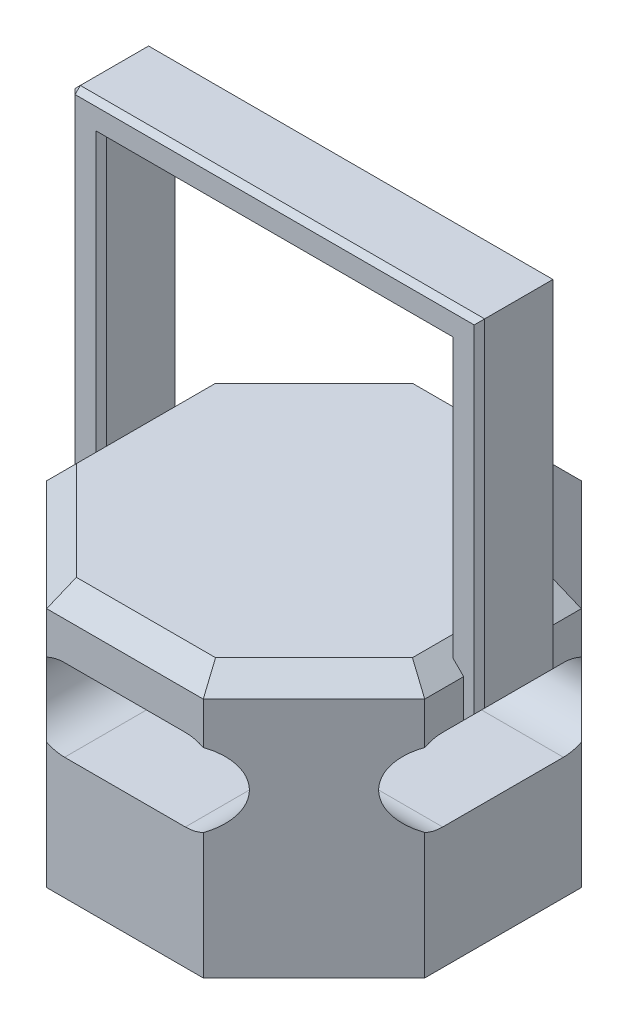
SolidWorks part; units mm, degrees
ref_plane "Front Plane" through (0, 0, 0) normal (0, 0, 1) x (1, 0, 0)
ref_plane "Top Plane" through (0, 0, 0) normal (0, 1, 0) x (1, 0, 0)
ref_plane "Right Plane" through (0, 0, 0) normal (1, 0, 0) x (0, 0, -1)
sketch "Sketch1" plane through (0, 0, 0) normal (0, 1, 0) x (1, 0, 0)
  line L1 (14.9117, 36) -> (-14.9117, 36)
  line L2 (-14.9117, 36) -> (-36, 14.9117)
  line L3 (-36, 14.9117) -> (-36, -14.9117)
  line L4 (-36, -14.9117) -> (-14.9117, -36)
  line L5 (-14.9117, -36) -> (14.9117, -36)
  line L6 (14.9117, -36) -> (36, -14.9117)
  line L7 (36, -14.9117) -> (36, 14.9117)
  line L8 (36, 14.9117) -> (14.9117, 36)
  circle A0 centre (0, 0) radius 36 construction
  dimension "D1" = 72
extrude "Boss-Extrude1" add sketch "Sketch1" along normal blind 50
sketch "Sketch18" plane through (0, 50, 0) normal (0, 1, 0) x (1, 0, 0)
  line L2 (-39, 7.5) -> (-39, -7.5)
  line L5 (-36, 14.9117) -> (-36, -14.9117) construction
  line L12 (-39, 7.5) -> (-33, 7.5)
  line L14 (-33, 7.5) -> (-33, -7.5)
  line L15 (-33, -7.5) -> (-39, -7.5)
  line L16 (0, -27.5) -> (0, 27.5) construction
  line L17 (33, 7.5) -> (33, -7.5)
  line L18 (39, 7.5) -> (33, 7.5)
  line L19 (39, 7.5) -> (39, -7.5)
  line L20 (33, -7.5) -> (39, -7.5)
  point P1 (-33, 0)
  dimension "D1" = 15
  dimension "D2" = 6
  dimension "D3" = 6
  dimension "D4" = 3
sketch "Sketch3" plane through (0, 0, 36) normal (0, 0, 1) x (1, 0, 0)
  line L0 (-11.5, 31) -> (11.5, 31) construction
  line L1 (-11.5, 38.8) -> (11.5, 38.8)
  line L2 (-11.5, 23.2) -> (11.5, 23.2)
  line L4 (-14.9117, 50) -> (14.9117, 50) construction
  arc A0 (-11.5, 38.8) -> (-11.5, 23.2) centre (-11.5, 31) ccw
  arc A1 (11.5, 23.2) -> (11.5, 38.8) centre (11.5, 31) ccw
  point P2 (0, 31)
  dimension "D1" = 7.8
  dimension "D2" = 23
  dimension "D3" = 19
extrude "Cut-Extrude1" cut sketch "Sketch3" against normal blind 72
sketch "Sketch4" plane through (-36, 0, 0) normal (-1, 0, 0) x (0, 0, 1)
  line L0 (-11.5, 31) -> (11.5, 31) construction
  line L1 (-11.5, 38.8) -> (11.5, 38.8)
  line L2 (-11.5, 23.2) -> (11.5, 23.2)
  line L4 (-14.9117, 50) -> (14.9117, 50) construction
  arc A0 (-11.5, 38.8) -> (-11.5, 23.2) centre (-11.5, 31) ccw
  arc A1 (11.5, 23.2) -> (11.5, 38.8) centre (11.5, 31) ccw
  point P2 (0, 31)
  dimension "D1" = 7.8
  dimension "D2" = 19
  dimension "D3" = 23
extrude "Cut-Extrude2" cut sketch "Sketch4" against normal up to surface (72 mm away) up to face at (36, 25, 0)
chamfer "Chamfer10" distance 4 angle 45 8 edges at (36, 50, 0) (25.4558, 50, 25.4558) (0, 50, 36) (-25.4558, 50, 25.4558) (-36, 50, 0) (-25.4558, 50, -25.4558) (0, 50, -36) (25.4558, 50, -25.4558)
extrude "Boss-Extrude10" add sketch "Sketch18" along normal blind 50 and the other way up to surface (11.2 mm away) separate body other way up to face at (0, 38.8, 0)
sketch "Sketch20" plane through (0, 100, 0) normal (0, 1, 0) x (1, 0, 0)
  line L1 (-39, 7.5) -> (39, 7.5)
  line L2 (-39, 7.5) -> (-39, -7.5)
  line L3 (-39, -7.5) -> (39, -7.5)
  line L4 (39, 7.5) -> (39, -7.5)
extrude "Boss-Extrude11" add sketch "Sketch20" along normal blind 6
chamfer "Chamfer8" distance 3 angle 45 2 edges at (-39, 38.8, 0) (39, 38.8, 0)
chamfer "Chamfer9" distance 1 angle 45 13 edges at (-33, 69.4, -7.5) (0, 100, -7.5) (33, 69.4, -7.5) (-33, 69.4, 7.5) (0, 100, 7.5) (33, 69.4, 7.5) (39, 73.9, -7.5) (0, 106, -7.5) (-39, 73.9, -7.5) (-39, 106, 0) (39, 73.9, 7.5) (0, 106, 7.5) (-39, 73.9, 7.5)
